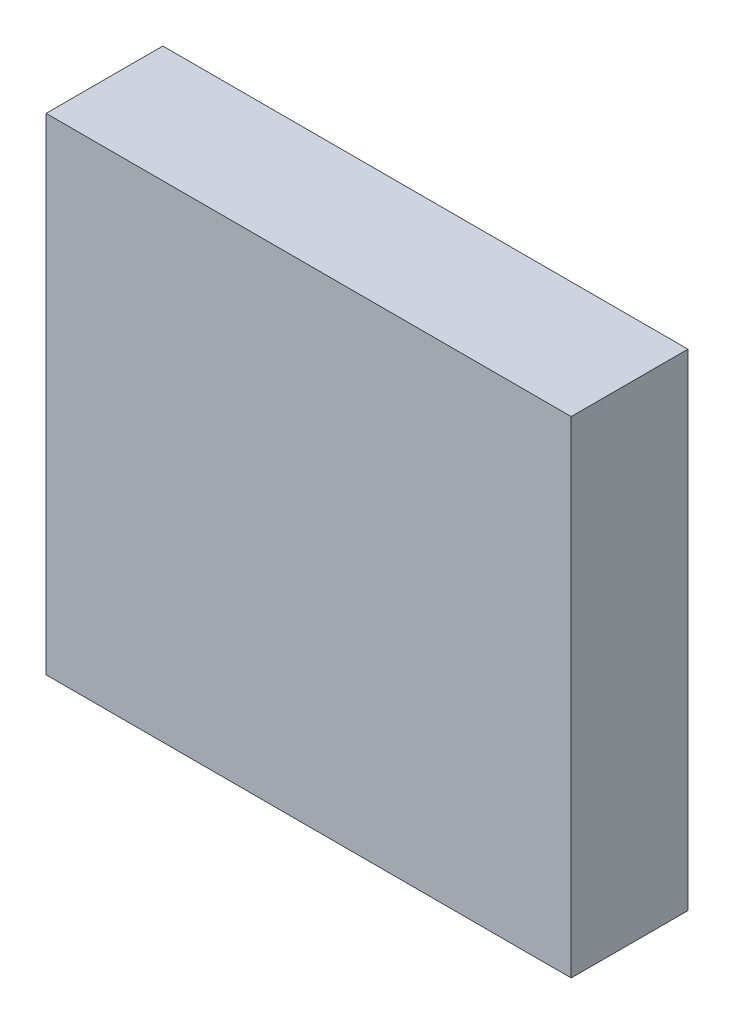
SolidWorks part; units mm, degrees
ref_plane "Front Plane" through (0, 0, 0) normal (0, 0, 1) x (1, 0, 0)
ref_plane "Top Plane" through (0, 0, 0) normal (0, 1, 0) x (1, 0, 0)
ref_plane "Right Plane" through (0, 0, 0) normal (1, 0, 0) x (0, 0, -1)
sketch "Sketch1" plane through (0, 0, 0) normal (0, 0, 1) x (1, 0, 0)
  line L1 (-5.4, 5) -> (5.4, 5)
  line L2 (-5.4, 5) -> (-5.4, -5)
  line L3 (-5.4, -5) -> (5.4, -5)
  line L4 (5.4, 5) -> (5.4, -5)
  line L5 (-5.4, 5) -> (5.4, -5) construction
  line L6 (-5.4, -5) -> (5.4, 5) construction
  point P0 (0, 0)
  dimension "D1" = 10.8
  dimension "D2" = 10
extrude "Boss-Extrude1" add sketch "Sketch1" along normal blind 2.4
sketch "Sketch2" plane through (0, -5, 0) normal (0, -1, 0) x (1, 0, 0)
  line L0 (0, 0) -> (0, 2.4) construction
  line L1 (-5.4, 2.4) -> (5.4, 2.4) construction
  line L2 (0, 1.2) -> (-1.27, 1.2) construction
  line L3 (-1.87, 1.8) -> (-0.67, 1.8)
  line L4 (-1.87, 1.8) -> (-1.87, 0.6)
  line L5 (-1.87, 0.6) -> (-0.67, 0.6)
  line L6 (-0.67, 1.8) -> (-0.67, 0.6)
  line L7 (-1.87, 1.8) -> (-0.67, 0.6) construction
  line L8 (-1.87, 0.6) -> (-0.67, 1.8) construction
  line L9 (-4.41, 1.8) -> (-3.21, 1.8)
  line L10 (-4.41, 1.8) -> (-4.41, 0.6)
  line L11 (-4.41, 0.6) -> (-3.21, 0.6)
  line L12 (-3.21, 1.8) -> (-3.21, 0.6)
  line L13 (-4.41, 1.8) -> (-3.21, 0.6) construction
  line L14 (-4.41, 0.6) -> (-3.21, 1.8) construction
  line L15 (-1.27, 1.2) -> (-3.81, 1.2) construction
  line L16 (1.87, 1.8) -> (1.87, 0.6)
  line L17 (1.87, 0.6) -> (0.67, 0.6)
  line L18 (0.67, 1.8) -> (0.67, 0.6)
  line L19 (1.87, 1.8) -> (0.67, 1.8)
  line L20 (4.41, 1.8) -> (4.41, 0.6)
  line L21 (4.41, 0.6) -> (3.21, 0.6)
  line L22 (3.21, 1.8) -> (3.21, 0.6)
  line L23 (4.41, 1.8) -> (3.21, 1.8)
  point P5 (-1.27, 1.2)
  point P10 (-3.81, 1.2)
  dimension "D1" = 1.27
  dimension "D2" = 2.54
  dimension "D3" = 1.2
extrude "Cut-Extrude1" cut sketch "Sketch2" against normal blind 2.8
